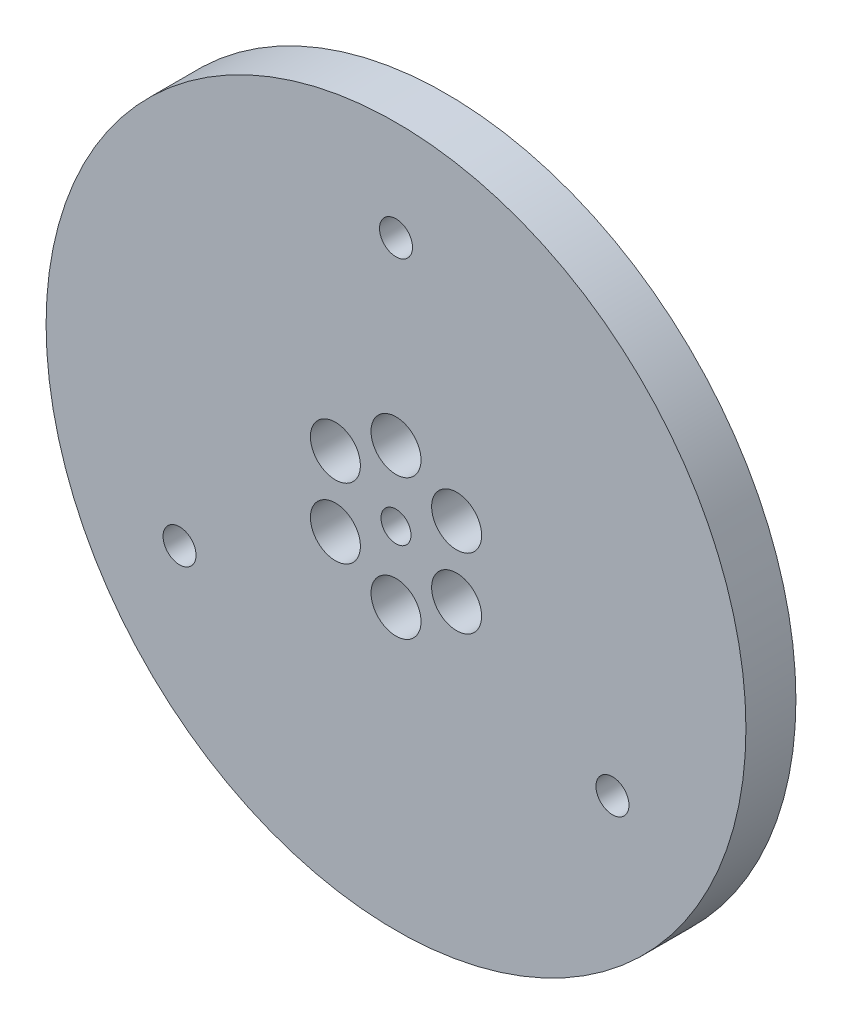
SolidWorks part; units mm, degrees
ref_plane "Front Plane" through (0, 0, 0) normal (0, 0, 1) x (1, 0, 0)
ref_plane "Top Plane" through (0, 0, 0) normal (0, 1, 0) x (1, 0, 0)
ref_plane "Right Plane" through (0, 0, 0) normal (1, 0, 0) x (0, 0, -1)
sketch "Sketch1" plane through (0, 0, 0) normal (0, 0, 1) x (1, 0, 0)
  circle A0 centre (0, 0) radius 35
  circle A2 centre (0, 0) radius 25 construction
  circle A3 centre (0, 25) radius 1.65
  circle A4 centre (21.6506, 12.5) radius 1.65 construction
  circle A5 centre (21.6506, -12.5) radius 1.65
  circle A6 centre (0, -25) radius 1.65 construction
  circle A7 centre (-21.6506, -12.5) radius 1.65
  circle A8 centre (-21.6506, 12.5) radius 1.65 construction
  circle A9 centre (0, 0) radius 7 construction
  circle A10 centre (0, 0) radius 1.5
  circle A11 centre (0, 7) radius 2.5
  circle A12 centre (6.0622, 3.5) radius 2.5
  circle A13 centre (6.0622, -3.5) radius 2.5
  circle A14 centre (0, -7) radius 2.5
  circle A15 centre (-6.0622, -3.5) radius 2.5
  circle A16 centre (-6.0622, 3.5) radius 2.5
  point P19 (0, 0)
  point P33 (0, 0)
  dimension "D1" = 70
  dimension "D2" = 14
  dimension "D3" = 10
  dimension "D4" = 3.3
  dimension "D6" = 6
  dimension "D7" = 5
  dimension "D8" = 3
  dimension "D5" = 6
extrude "Boss-Extrude1" add sketch "Sketch1" along normal blind 5
